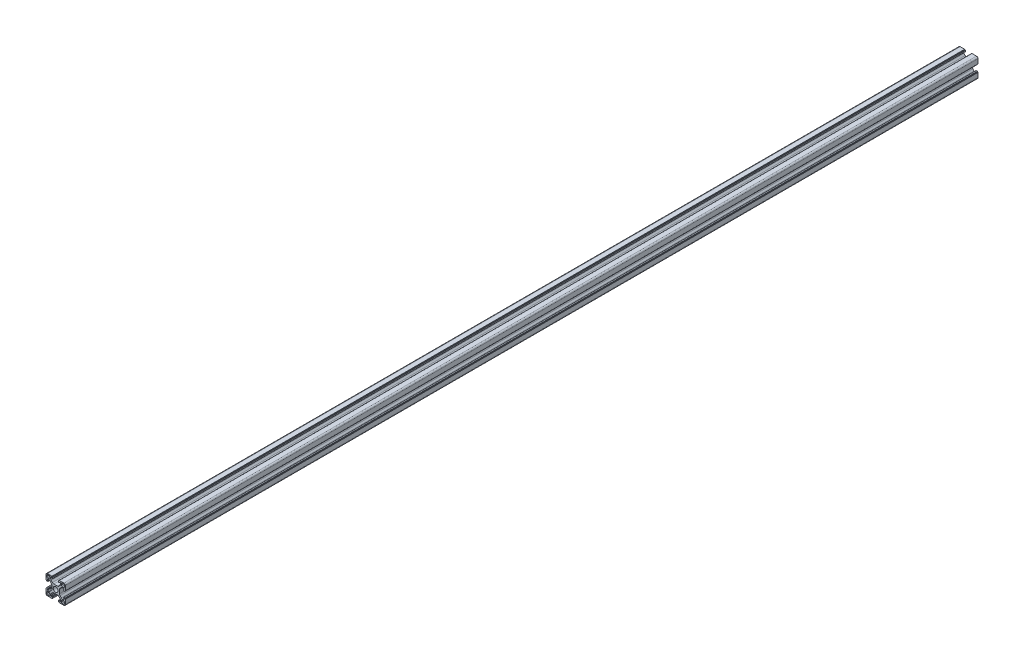
SolidWorks part; units mm, degrees
material "1060 Сплав"
ref_plane "Спереди" through (0, 0, 0) normal (0, 0, 1) x (1, 0, 0)
ref_plane "Сверху" through (0, 0, 0) normal (0, 1, 0) x (1, 0, 0)
ref_plane "Справа" through (0, 0, 0) normal (1, 0, 0) x (0, 0, -1)
sketch "Эскиз2" plane through (0, 0, 0) normal (0, 0, 1) x (1, 0, 0)
  line L0 (9.2299, 9.7837) -> (6.2299, 6.7837) construction
  line L1 (0.1299, 4.6837) -> (2.0286, 4.6837)
  line L2 (0.1299, 0.6837) -> (10.1299, 10.6837) construction
  line L3 (7.7299, 8.2837) -> (6.2299, 9.7837) construction
  line L4 (3.4428, 5.2695) -> (4.7441, 6.5707)
  line L5 (7.0299, 6.7837) -> (8.4299, 6.7837)
  line L6 (6.2299, 7.5837) -> (6.2299, 8.9837)
  line L7 (8.4299, 9.7837) -> (7.0299, 9.7837)
  line L8 (5.3299, 8.8837) -> (5.3299, 7.9849)
  line L9 (3.8931, 8.757) -> (4.3734, 9.2373)
  line L10 (3.3299, 10.2328) -> (3.8299, 10.2328)
  line L11 (3.7163, 8.6837) -> (3.4299, 8.6837)
  line L12 (4.727, 9.3837) -> (4.8299, 9.3837)
  line L13 (3.8299, 10.5337) -> (3.8299, 10.2328)
  line L14 (3.1799, 10.0828) -> (3.1799, 8.9337)
  line L15 (8.6299, 10.6837) -> (3.9799, 10.6837)
  line L16 (9.2299, 8.9837) -> (9.2299, 7.5837)
  line L17 (10.1299, 9.1837) -> (10.1299, 4.5337)
  line L18 (9.5289, 3.7337) -> (8.3799, 3.7337)
  line L19 (9.9799, 4.3837) -> (9.6789, 4.3837)
  line L20 (8.8299, 5.2808) -> (8.8299, 5.3837)
  line L21 (8.1299, 4.2702) -> (8.1299, 3.9837)
  line L22 (9.6789, 3.8837) -> (9.6789, 4.3837)
  line L23 (8.2031, 4.447) -> (8.6834, 4.9273)
  line L24 (8.3299, 5.8837) -> (7.4311, 5.8837)
  line L25 (4.7156, 3.9967) -> (6.0169, 5.2979)
  line L26 (4.1299, 0.6837) -> (4.1299, 2.5825)
  line L27 (4.1299, 0.6837) -> (4.1299, -1.2151)
  line L28 (4.7156, -2.6293) -> (6.0169, -3.9305)
  line L29 (6.2299, -6.2163) -> (6.2299, -7.6163)
  line L30 (7.0299, -5.4163) -> (8.4299, -5.4163)
  line L31 (9.2299, -7.6163) -> (9.2299, -6.2163)
  line L32 (8.3299, -4.5163) -> (7.4311, -4.5163)
  line L33 (8.2031, -3.0795) -> (8.6834, -3.5598)
  line L34 (9.6789, -2.5163) -> (9.6789, -3.0163)
  line L35 (8.1299, -2.9027) -> (8.1299, -2.6163)
  line L36 (8.8299, -3.9134) -> (8.8299, -4.0163)
  line L37 (9.9799, -3.0163) -> (9.6789, -3.0163)
  line L38 (9.5289, -2.3663) -> (8.3799, -2.3663)
  line L39 (10.1299, -7.8163) -> (10.1299, -3.1663)
  line L40 (8.4299, -8.4163) -> (7.0299, -8.4163)
  line L41 (8.6299, -9.3163) -> (3.9799, -9.3163)
  line L42 (3.1799, -8.7153) -> (3.1799, -7.5663)
  line L43 (3.8299, -9.1663) -> (3.8299, -8.8653)
  line L44 (4.727, -8.0163) -> (4.8299, -8.0163)
  line L45 (3.7163, -7.3163) -> (3.4299, -7.3163)
  line L46 (3.3299, -8.8653) -> (3.8299, -8.8653)
  line L47 (3.8931, -7.3895) -> (4.3734, -7.8698)
  line L48 (5.3299, -7.5163) -> (5.3299, -6.6175)
  line L49 (3.4428, -3.9021) -> (4.7441, -5.2033)
  line L50 (0.1299, -3.3163) -> (2.0286, -3.3163)
  line L51 (9.2299, -8.4163) -> (6.2299, -5.4163) construction
  line L52 (0.1299, 0.6837) -> (10.1299, -9.3163) construction
  line L53 (7.7299, -6.9163) -> (9.2299, -5.4163) construction
  line L54 (0.1299, -3.3163) -> (-1.7689, -3.3163)
  line L55 (-3.1831, -3.9021) -> (-4.4844, -5.2033)
  line L56 (-6.7701, -5.4163) -> (-8.1701, -5.4163)
  line L57 (-5.9701, -6.2163) -> (-5.9701, -7.6163)
  line L58 (-8.1701, -8.4163) -> (-6.7701, -8.4163)
  line L59 (-5.0701, -7.5163) -> (-5.0701, -6.6175)
  line L60 (-3.6334, -7.3895) -> (-4.1137, -7.8698)
  line L61 (-3.0701, -8.8653) -> (-3.5701, -8.8653)
  line L62 (-3.4566, -7.3163) -> (-3.1701, -7.3163)
  line L63 (-4.4673, -8.0163) -> (-4.5701, -8.0163)
  line L64 (-3.5701, -9.1663) -> (-3.5701, -8.8653)
  line L65 (-2.9201, -8.7153) -> (-2.9201, -7.5663)
  line L66 (-8.3701, -9.3163) -> (-3.7201, -9.3163)
  line L67 (-8.9701, -7.6163) -> (-8.9701, -6.2163)
  line L68 (-9.8701, -7.8163) -> (-9.8701, -3.1663)
  line L69 (-9.2692, -2.3663) -> (-8.1201, -2.3663)
  line L70 (-9.7201, -3.0163) -> (-9.4192, -3.0163)
  line L71 (-8.5701, -3.9134) -> (-8.5701, -4.0163)
  line L72 (-7.8701, -2.9027) -> (-7.8701, -2.6163)
  line L73 (-9.4192, -2.5163) -> (-9.4192, -3.0163)
  line L74 (-7.9434, -3.0795) -> (-8.4237, -3.5598)
  line L75 (-8.0701, -4.5163) -> (-7.1714, -4.5163)
  line L76 (-4.4559, -2.6293) -> (-5.7572, -3.9305)
  line L77 (-3.8701, 0.6837) -> (-3.8701, -1.2151)
  line L78 (-8.9701, -8.4163) -> (-5.9701, -5.4163) construction
  line L79 (0.1299, 0.6837) -> (-9.8701, -9.3163) construction
  line L80 (-7.4701, -6.9163) -> (-5.9701, -8.4163) construction
  line L81 (-3.8701, 0.6837) -> (-3.8701, 2.5825)
  line L82 (-4.4559, 3.9967) -> (-5.7572, 5.2979)
  line L83 (-5.9701, 7.5837) -> (-5.9701, 8.9837)
  line L84 (-6.7701, 6.7837) -> (-8.1701, 6.7837)
  line L85 (-8.9701, 8.9837) -> (-8.9701, 7.5837)
  line L86 (-8.0701, 5.8837) -> (-7.1714, 5.8837)
  line L87 (-7.9434, 4.447) -> (-8.4237, 4.9273)
  line L88 (-9.4192, 3.8837) -> (-9.4192, 4.3837)
  line L89 (-7.8701, 4.2702) -> (-7.8701, 3.9837)
  line L90 (-8.5701, 5.2808) -> (-8.5701, 5.3837)
  line L91 (-9.7201, 4.3837) -> (-9.4192, 4.3837)
  line L92 (-9.2692, 3.7337) -> (-8.1201, 3.7337)
  line L93 (-9.8701, 9.1837) -> (-9.8701, 4.5337)
  line L94 (-8.1701, 9.7837) -> (-6.7701, 9.7837)
  line L95 (-8.3701, 10.6837) -> (-3.7201, 10.6837)
  line L96 (-2.9201, 10.0828) -> (-2.9201, 8.9337)
  line L97 (-3.5701, 10.5337) -> (-3.5701, 10.2328)
  line L98 (-4.4673, 9.3837) -> (-4.5701, 9.3837)
  line L99 (-3.4566, 8.6837) -> (-3.1701, 8.6837)
  line L100 (-3.0701, 10.2328) -> (-3.5701, 10.2328)
  line L101 (-3.6334, 8.757) -> (-4.1137, 9.2373)
  line L102 (-5.0701, 8.8837) -> (-5.0701, 7.9849)
  line L103 (-3.1831, 5.2695) -> (-4.4844, 6.5707)
  line L104 (0.1299, 4.6837) -> (-1.7689, 4.6837)
  line L105 (-11.6342, 0.6837) -> (11.6342, 0.6837) construction
  line L106 (-8.9701, 9.7837) -> (-5.9701, 6.7837) construction
  line L107 (0.1299, -11.4027) -> (0.1299, 11.4027) construction
  line L108 (0.1299, 0.6837) -> (-9.8701, 10.6837) construction
  line L109 (-7.4701, 8.2837) -> (-8.9701, 6.7837) construction
  arc A0 (9.2299, 8.9837) -> (8.4299, 9.7837) centre (8.4299, 8.9837) ccw
  arc A1 (7.0299, 9.7837) -> (6.2299, 8.9837) centre (7.0299, 8.9837) ccw
  arc A2 (7.0299, 6.7837) -> (6.2299, 7.5837) centre (7.0299, 7.5837) cw
  arc A3 (8.6299, 10.6837) -> (10.1299, 9.1837) centre (8.6299, 9.1837) cw
  arc A4 (3.3299, 10.2328) -> (3.1799, 10.0828) centre (3.3299, 10.0828) ccw
  arc A5 (3.9799, 10.6837) -> (3.8299, 10.5337) centre (3.9799, 10.5337) ccw
  arc A6 (3.7163, 8.6837) -> (3.8931, 8.757) centre (3.7163, 8.9337) ccw
  arc A7 (3.4299, 8.6837) -> (3.1799, 8.9337) centre (3.4299, 8.9337) cw
  arc A8 (4.3734, 9.2373) -> (4.727, 9.3837) centre (4.727, 8.8837) cw
  arc A9 (4.8299, 9.3837) -> (5.3299, 8.8837) centre (4.8299, 8.8837) cw
  arc A10 (2.6299, 0.6837) -> (0.1299, 3.1837) centre (0.1299, 0.6837) ccw
  arc A11 (2.0286, 4.6837) -> (3.4428, 5.2695) centre (2.0286, 6.6837) ccw
  arc A12 (5.3299, 7.9849) -> (4.7441, 6.5707) centre (3.3299, 7.9849) cw
  arc A13 (9.2299, 7.5837) -> (8.4299, 6.7837) centre (8.4299, 7.5837) cw
  arc A14 (8.8299, 5.3837) -> (8.3299, 5.8837) centre (8.3299, 5.3837) ccw
  arc A15 (8.6834, 4.9273) -> (8.8299, 5.2808) centre (8.3299, 5.2808) ccw
  arc A16 (8.1299, 3.9837) -> (8.3799, 3.7337) centre (8.3799, 3.9837) ccw
  arc A17 (8.1299, 4.2702) -> (8.2031, 4.447) centre (8.3799, 4.2702) cw
  arc A18 (10.1299, 4.5337) -> (9.9799, 4.3837) centre (9.9799, 4.5337) cw
  arc A19 (9.6789, 3.8837) -> (9.5289, 3.7337) centre (9.5289, 3.8837) cw
  arc A20 (7.4311, 5.8837) -> (6.0169, 5.2979) centre (7.4311, 3.8837) ccw
  arc A21 (4.1299, 2.5825) -> (4.7156, 3.9967) centre (6.1299, 2.5825) cw
  arc A22 (8.4299, -8.4163) -> (9.2299, -7.6163) centre (8.4299, -7.6163) ccw
  arc A23 (9.2299, -6.2163) -> (8.4299, -5.4163) centre (8.4299, -6.2163) ccw
  arc A24 (6.2299, -6.2163) -> (7.0299, -5.4163) centre (7.0299, -6.2163) cw
  arc A25 (10.1299, -7.8163) -> (8.6299, -9.3163) centre (8.6299, -7.8163) cw
  arc A26 (9.6789, -2.5163) -> (9.5289, -2.3663) centre (9.5289, -2.5163) ccw
  arc A27 (10.1299, -3.1663) -> (9.9799, -3.0163) centre (9.9799, -3.1663) ccw
  arc A28 (8.1299, -2.9027) -> (8.2031, -3.0795) centre (8.3799, -2.9027) ccw
  arc A29 (8.1299, -2.6163) -> (8.3799, -2.3663) centre (8.3799, -2.6163) cw
  arc A30 (8.6834, -3.5598) -> (8.8299, -3.9134) centre (8.3299, -3.9134) cw
  arc A31 (8.8299, -4.0163) -> (8.3299, -4.5163) centre (8.3299, -4.0163) cw
  arc A32 (0.1299, -1.8163) -> (2.6299, 0.6837) centre (0.1299, 0.6837) ccw
  arc A33 (4.1299, -1.2151) -> (4.7156, -2.6293) centre (6.1299, -1.2151) ccw
  arc A34 (7.4311, -4.5163) -> (6.0169, -3.9305) centre (7.4311, -2.5163) cw
  arc A35 (7.0299, -8.4163) -> (6.2299, -7.6163) centre (7.0299, -7.6163) cw
  arc A36 (4.8299, -8.0163) -> (5.3299, -7.5163) centre (4.8299, -7.5163) ccw
  arc A37 (4.3734, -7.8698) -> (4.727, -8.0163) centre (4.727, -7.5163) ccw
  arc A38 (3.4299, -7.3163) -> (3.1799, -7.5663) centre (3.4299, -7.5663) ccw
  arc A39 (3.7163, -7.3163) -> (3.8931, -7.3895) centre (3.7163, -7.5663) cw
  arc A40 (3.9799, -9.3163) -> (3.8299, -9.1663) centre (3.9799, -9.1663) cw
  arc A41 (3.3299, -8.8653) -> (3.1799, -8.7153) centre (3.3299, -8.7153) cw
  arc A42 (5.3299, -6.6175) -> (4.7441, -5.2033) centre (3.3299, -6.6175) ccw
  arc A43 (2.0286, -3.3163) -> (3.4428, -3.9021) centre (2.0286, -5.3163) cw
  arc A44 (-8.9701, -7.6163) -> (-8.1701, -8.4163) centre (-8.1701, -7.6163) ccw
  arc A45 (-6.7701, -8.4163) -> (-5.9701, -7.6163) centre (-6.7701, -7.6163) ccw
  arc A46 (-6.7701, -5.4163) -> (-5.9701, -6.2163) centre (-6.7701, -6.2163) cw
  arc A47 (-8.3701, -9.3163) -> (-9.8701, -7.8163) centre (-8.3701, -7.8163) cw
  arc A48 (-3.0701, -8.8653) -> (-2.9201, -8.7153) centre (-3.0701, -8.7153) ccw
  arc A49 (-3.7201, -9.3163) -> (-3.5701, -9.1663) centre (-3.7201, -9.1663) ccw
  arc A50 (-3.4566, -7.3163) -> (-3.6334, -7.3895) centre (-3.4566, -7.5663) ccw
  arc A51 (-3.1701, -7.3163) -> (-2.9201, -7.5663) centre (-3.1701, -7.5663) cw
  arc A52 (-4.1137, -7.8698) -> (-4.4673, -8.0163) centre (-4.4673, -7.5163) cw
  arc A53 (-4.5701, -8.0163) -> (-5.0701, -7.5163) centre (-4.5701, -7.5163) cw
  arc A54 (-2.3701, 0.6837) -> (0.1299, -1.8163) centre (0.1299, 0.6837) ccw
  arc A55 (-1.7689, -3.3163) -> (-3.1831, -3.9021) centre (-1.7689, -5.3163) ccw
  arc A56 (-5.0701, -6.6175) -> (-4.4844, -5.2033) centre (-3.0701, -6.6175) cw
  arc A57 (-8.9701, -6.2163) -> (-8.1701, -5.4163) centre (-8.1701, -6.2163) cw
  arc A58 (-8.5701, -4.0163) -> (-8.0701, -4.5163) centre (-8.0701, -4.0163) ccw
  arc A59 (-8.4237, -3.5598) -> (-8.5701, -3.9134) centre (-8.0701, -3.9134) ccw
  arc A60 (-7.8701, -2.6163) -> (-8.1201, -2.3663) centre (-8.1201, -2.6163) ccw
  arc A61 (-7.8701, -2.9027) -> (-7.9434, -3.0795) centre (-8.1201, -2.9027) cw
  arc A62 (-9.8701, -3.1663) -> (-9.7201, -3.0163) centre (-9.7201, -3.1663) cw
  arc A63 (-9.4192, -2.5163) -> (-9.2692, -2.3663) centre (-9.2692, -2.5163) cw
  arc A64 (-7.1714, -4.5163) -> (-5.7572, -3.9305) centre (-7.1714, -2.5163) ccw
  arc A65 (-3.8701, -1.2151) -> (-4.4559, -2.6293) centre (-5.8701, -1.2151) cw
  arc A66 (-8.1701, 9.7837) -> (-8.9701, 8.9837) centre (-8.1701, 8.9837) ccw
  arc A67 (-8.9701, 7.5837) -> (-8.1701, 6.7837) centre (-8.1701, 7.5837) ccw
  arc A68 (-5.9701, 7.5837) -> (-6.7701, 6.7837) centre (-6.7701, 7.5837) cw
  arc A69 (-9.8701, 9.1837) -> (-8.3701, 10.6837) centre (-8.3701, 9.1837) cw
  arc A70 (-9.4192, 3.8837) -> (-9.2692, 3.7337) centre (-9.2692, 3.8837) ccw
  arc A71 (-9.8701, 4.5337) -> (-9.7201, 4.3837) centre (-9.7201, 4.5337) ccw
  arc A72 (-7.8701, 4.2702) -> (-7.9434, 4.447) centre (-8.1201, 4.2702) ccw
  arc A73 (-7.8701, 3.9837) -> (-8.1201, 3.7337) centre (-8.1201, 3.9837) cw
  arc A74 (-8.4237, 4.9273) -> (-8.5701, 5.2808) centre (-8.0701, 5.2808) cw
  arc A75 (-8.5701, 5.3837) -> (-8.0701, 5.8837) centre (-8.0701, 5.3837) cw
  arc A76 (0.1299, 3.1837) -> (-2.3701, 0.6837) centre (0.1299, 0.6837) ccw
  arc A77 (-3.8701, 2.5825) -> (-4.4559, 3.9967) centre (-5.8701, 2.5825) ccw
  arc A78 (-7.1714, 5.8837) -> (-5.7572, 5.2979) centre (-7.1714, 3.8837) cw
  arc A79 (-6.7701, 9.7837) -> (-5.9701, 8.9837) centre (-6.7701, 8.9837) cw
  arc A80 (-4.5701, 9.3837) -> (-5.0701, 8.8837) centre (-4.5701, 8.8837) ccw
  arc A81 (-4.1137, 9.2373) -> (-4.4673, 9.3837) centre (-4.4673, 8.8837) ccw
  arc A82 (-3.1701, 8.6837) -> (-2.9201, 8.9337) centre (-3.1701, 8.9337) ccw
  arc A83 (-3.4566, 8.6837) -> (-3.6334, 8.757) centre (-3.4566, 8.9337) cw
  arc A84 (-3.7201, 10.6837) -> (-3.5701, 10.5337) centre (-3.7201, 10.5337) cw
  arc A85 (-3.0701, 10.2328) -> (-2.9201, 10.0828) centre (-3.0701, 10.0828) cw
  arc A86 (-5.0701, 7.9849) -> (-4.4844, 6.5707) centre (-3.0701, 7.9849) ccw
  arc A87 (-1.7689, 4.6837) -> (-3.1831, 5.2695) centre (-1.7689, 6.6837) cw
  point P0 (0.1299, 0.6837)
  point P9 (0.1299, 0.6837)
  point P40 (8.8299, 4.3837)
  point P93 (3.8299, -8.0163)
  point P144 (3.8299, 9.3837)
  point P152 (8.8299, -3.0163)
  point P153 (0.1299, -3.2405)
  point P154 (0.1299, 0.6837)
  point P189 (-8.5701, -3.0163)
  point P228 (-3.5701, -8.0163)
  point P229 (-3.7944, 0.6837)
  point P230 (0.1299, 0.6837)
  point P268 (-3.5701, 9.3837)
  point P273 (4.0541, 0.6837)
  point P306 (-8.5701, 4.3837)
  point P307 (0.1299, 4.608)
  point P309 (0.1299, 0.6837)
  dimension "D3" = 5
  dimension "D6" = 2
  dimension "D1" = 2
  dimension "D2" = 6
  dimension "D4" = 4
  dimension "D5" = 0.9
extrude "Бобышка-Вытянуть1" add sketch "Эскиз2" along normal blind 945
